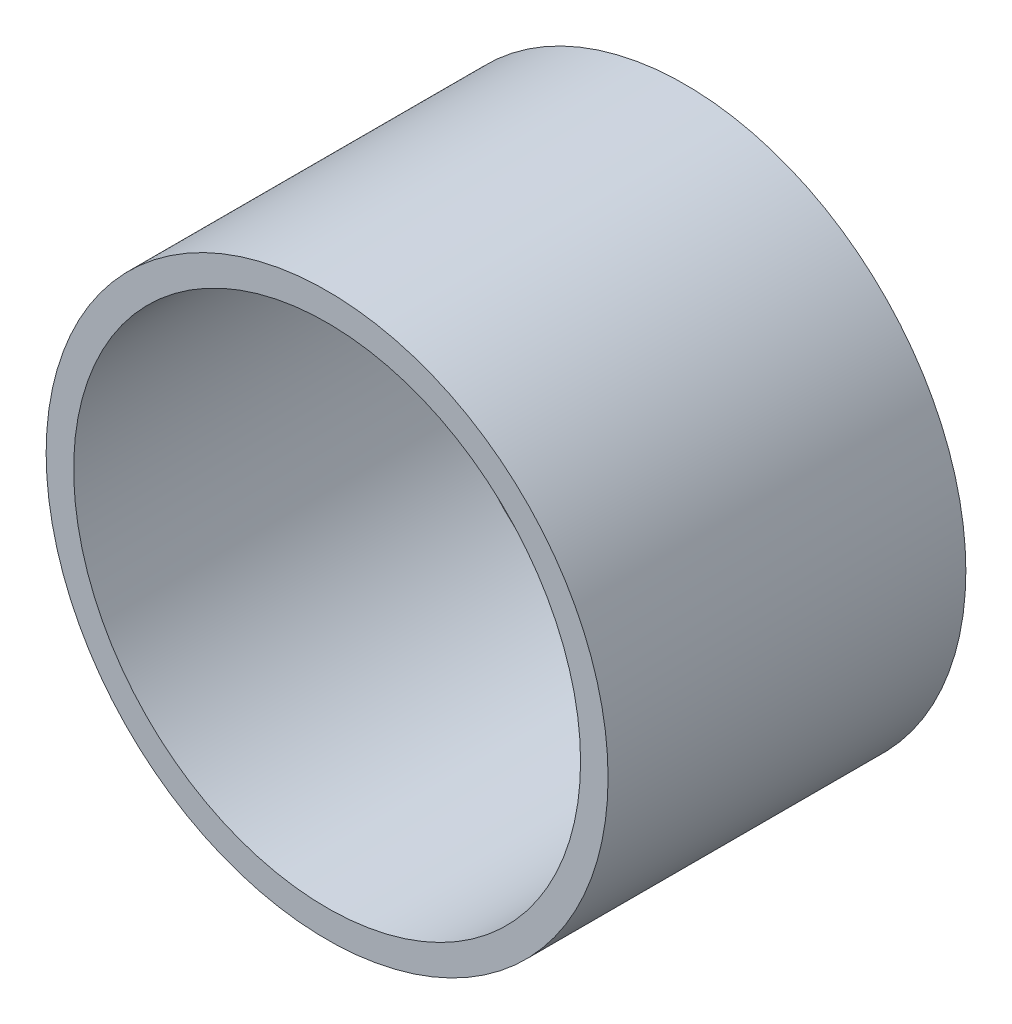
SolidWorks part; units mm, degrees
ref_plane "Front Plane" through (0, 0, 0) normal (0, 0, 1) x (1, 0, 0)
ref_plane "Top Plane" through (0, 0, 0) normal (0, 1, 0) x (1, 0, 0)
ref_plane "Right Plane" through (0, 0, 0) normal (1, 0, 0) x (0, 0, -1)
sketch "Sketch1" plane through (0, 0, 0) normal (0, 0, 1) x (1, 0, 0)
  circle A0 centre (0, 0) radius 6.096
  dimension "D1" = 12.192
extrude "Boss-Extrude1" add sketch "Sketch1" along normal blind 7.7624
sketch "Sketch4" plane through (0, 0, 7.7624) normal (0, 0, 1) x (1, 0, 0)
  circle A0 centre (0, 0) radius 5.4991
  dimension "D1" = 10.9982
extrude "Cut-Extrude1" cut sketch "Sketch4" against normal blind 14.346
